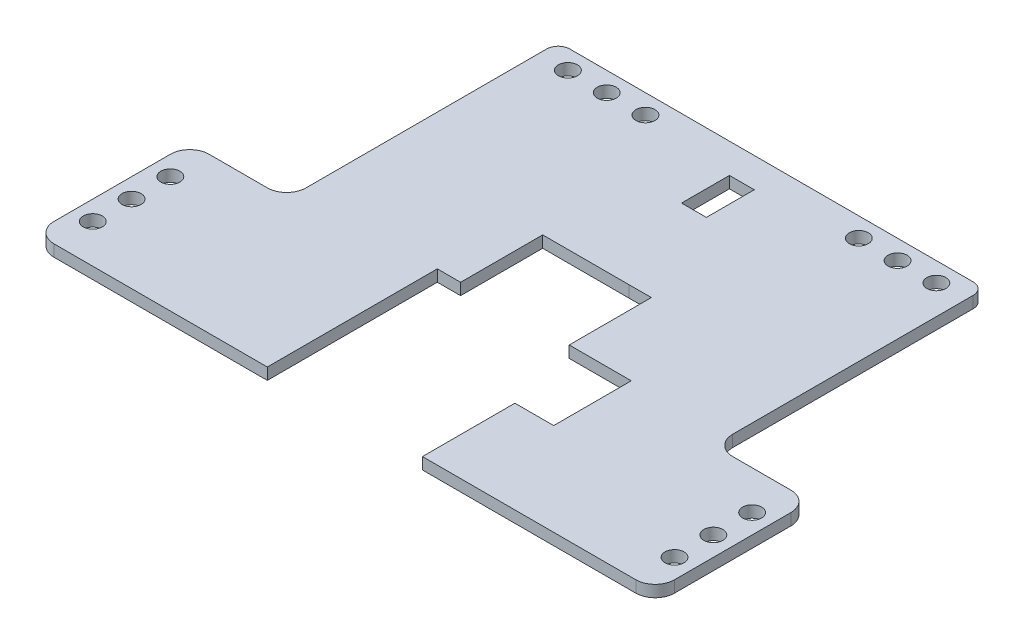
SolidWorks part; units mm, degrees
ref_plane "Front Plane" through (0, 0, 0) normal (0, 0, 1) x (1, 0, 0)
ref_plane "Top Plane" through (0, 0, 0) normal (0, 1, 0) x (1, 0, 0)
ref_plane "Right Plane" through (0, 0, 0) normal (1, 0, 0) x (0, 0, -1)
ref_plane "Plane1" through (-80, 40, 5) normal (0, -1, 0) x (-1, 0, 0)
sketch "Sketch2" plane through (0, 40, 0) normal (0, 1, 0) x (1, 0, 0)
  line L1 (20, -16.1649) -> (20, -40)
  line L4 (3.2, 50) -> (-3.2, 50)
  line L5 (-20, -40) -> (-20, 3.8351)
  line L6 (20, 3.8351) -> (30, 3.8351)
  line L8 (20, -16.1649) -> (30, -16.1649)
  line L9 (30, 3.8351) -> (30, -16.1649)
  line L10 (20, 3.8351) -> (14, 3.8351)
  line L11 (-14, 25) -> (8.2898, 25)
  line L13 (-20, 3.8351) -> (-14, 3.8351)
  line L14 (-20, 3.8351) -> (-8, 3.8351) construction
  line L15 (-14, 3.8351) -> (-14, 25)
  line L16 (14, 3.8351) -> (14, 25.023)
  line L17 (38.338, 25.023) -> (12.29, 25.023) construction
  line L18 (14, 25.023) -> (8.2898, 25)
  line L30 (45, 55) -> (45, -5)
  line L31 (50, -10) -> (65, -10)
  line L35 (20, -40) -> (75, -40)
  line L36 (80, -35) -> (80, -5)
  line L37 (75, 0) -> (60, 0)
  line L38 (55, 5) -> (55, 67)
  line L39 (52, 70) -> (10, 70)
  line L40 (10, 70) -> (-10, 70)
  line L111 (45, 55) -> (45, -5)
  line L112 (50, -10) -> (65, -10)
  line L113 (70, -15) -> (70, -25)
  line L114 (65, -30) -> (20, -30)
  line L115 (20, -30) -> (20, -40)
  line L116 (20, -40) -> (75, -40)
  line L117 (80, -35) -> (80, -5)
  line L118 (75, 0) -> (60, 0)
  line L119 (55, 5) -> (55, 67)
  line L120 (52, 70) -> (10, 70)
  line L121 (10, 70) -> (-10, 70)
  line L122 (-10, 70) -> (-52, 70)
  line L123 (-55, 67) -> (-55, 5)
  line L124 (-60, 0) -> (-75, 0)
  line L125 (-80, -5) -> (-80, -35)
  line L126 (-75, -40) -> (-20, -40)
  line L127 (-20, -40) -> (-20, -30)
  line L128 (-20, -30) -> (-65, -30)
  line L129 (-70, -25) -> (-70, -15)
  line L130 (-65, -10) -> (-50, -10)
  line L131 (-45, -5) -> (-45, 55)
  line L132 (-40, 60) -> (-15, 60)
  line L133 (-10, 55) -> (-10, 50)
  line L134 (-10, 50) -> (-3.2, 50)
  line L135 (-3.2, 50) -> (-3.2, 62.35)
  line L136 (-3.2, 62.35) -> (3.2, 62.35)
  line L137 (3.2, 62.35) -> (3.2, 50)
  line L138 (3.2, 50) -> (10, 50)
  line L139 (10, 50) -> (10, 55)
  line L140 (15, 60) -> (40, 60)
  line L146 (20, -40) -> (75, -40)
  line L147 (80, -35) -> (80, -5)
  line L148 (75, 0) -> (60, 0)
  line L149 (55, 5) -> (55, 67)
  line L150 (52, 70) -> (10, 70)
  line L151 (10, 70) -> (-10, 70)
  line L152 (-10, 70) -> (-52, 70)
  line L153 (-55, 67) -> (-55, 5)
  line L154 (-60, 0) -> (-75, 0)
  line L155 (-80, -5) -> (-80, -35)
  line L156 (-75, -40) -> (-20, -40)
  line L165 (-3.2, 50) -> (-3.2, 62.35)
  line L166 (-3.2, 62.35) -> (3.2, 62.35)
  line L167 (3.2, 62.35) -> (3.2, 50)
  line L174 (70, -15) -> (70, -25)
  line L175 (65, -30) -> (20, -30)
  line L176 (20, -30) -> (20, -40)
  line L178 (-10, 70) -> (-52, 70)
  line L180 (-55, 67) -> (-55, 5)
  line L182 (-60, 0) -> (-75, 0)
  line L184 (-80, -5) -> (-80, -35)
  line L186 (-75, -40) -> (-20, -40)
  line L188 (-20, -40) -> (-20, -30)
  line L190 (-20, -30) -> (-65, -30)
  line L191 (-70, -25) -> (-70, -15)
  line L192 (-65, -10) -> (-50, -10)
  line L193 (-45, -5) -> (-45, 55)
  line L194 (-40, 60) -> (-15, 60)
  line L195 (-10, 55) -> (-10, 50)
  line L196 (-10, 50) -> (-3.2, 50)
  line L197 (-3.2, 50) -> (-3.2, 62.35)
  line L198 (-3.2, 50) -> (-3.2, 62.35)
  line L199 (-3.2, 62.35) -> (3.2, 62.35)
  line L200 (-3.2, 62.35) -> (3.2, 62.35)
  line L201 (3.2, 62.35) -> (3.2, 50)
  line L202 (3.2, 62.35) -> (3.2, 50)
  line L203 (3.2, 50) -> (10, 50)
  line L204 (10, 50) -> (10, 55)
  line L205 (15, 60) -> (40, 60)
  circle A6 centre (47.5, 65) radius 2.45 construction
  circle A7 centre (37.5, 65) radius 2.45 construction
  circle A8 centre (27.5, 65) radius 2.45 construction
  circle A9 centre (-47.5, 65) radius 2.45 construction
  circle A10 centre (-37.5, 65) radius 2.45 construction
  circle A11 centre (-27.5, 65) radius 2.45 construction
  circle A54 centre (47.5, 65) radius 2.45
  circle A55 centre (37.5, 65) radius 2.45
  circle A56 centre (27.5, 65) radius 2.45
  circle A57 centre (-47.5, 65) radius 2.45
  circle A58 centre (-37.5, 65) radius 2.45
  circle A59 centre (-27.5, 65) radius 2.45
  circle A60 centre (-75, -30) radius 2.45 construction
  circle A61 centre (-75, -20) radius 2.45 construction
  circle A62 centre (-75, -10) radius 2.45 construction
  circle A63 centre (75, -30) radius 2.45 construction
  circle A64 centre (75, -20) radius 2.45 construction
  circle A65 centre (75, -10) radius 2.45 construction
  circle A66 centre (-75, -30) radius 2.45
  circle A67 centre (-75, -20) radius 2.45
  circle A68 centre (-75, -10) radius 2.45
  circle A69 centre (75, -30) radius 2.45
  circle A70 centre (75, -20) radius 2.45
  circle A71 centre (75, -10) radius 2.45
  arc A90 (45, -5) -> (50, -10) centre (50, -5) ccw
  arc A91 (70, -15) -> (65, -10) centre (65, -15) ccw
  arc A92 (65, -30) -> (70, -25) centre (65, -25) ccw
  arc A93 (75, -40) -> (80, -35) centre (75, -35) ccw
  arc A94 (80, -5) -> (75, 0) centre (75, -5) ccw
  arc A95 (55, 5) -> (60, 0) centre (60, 5) ccw
  arc A96 (45, -5) -> (50, -10) centre (50, -5) ccw
  arc A97 (70, -15) -> (65, -10) centre (65, -15) ccw
  arc A98 (65, -30) -> (70, -25) centre (65, -25) ccw
  arc A99 (75, -40) -> (80, -35) centre (75, -35) ccw
  arc A101 (80, -5) -> (75, 0) centre (75, -5) ccw
  arc A103 (55, 5) -> (60, 0) centre (60, 5) ccw
  arc A109 (-60, 0) -> (-55, 5) centre (-60, 5) ccw
  arc A111 (-75, 0) -> (-80, -5) centre (-75, -5) ccw
  arc A113 (-80, -35) -> (-75, -40) centre (-75, -35) ccw
  arc A115 (-70, -25) -> (-65, -30) centre (-65, -25) ccw
  arc A116 (-65, -10) -> (-70, -15) centre (-65, -15) ccw
  arc A117 (-50, -10) -> (-45, -5) centre (-50, -5) ccw
  arc A118 (-40, 60) -> (-45, 55) centre (-40, 55) ccw
  arc A119 (-10, 55) -> (-15, 60) centre (-15, 55) ccw
  arc A120 (15, 60) -> (10, 55) centre (15, 55) ccw
  arc A121 (45, 55) -> (40, 60) centre (40, 55) ccw
  arc A122 (-52, 70) -> (-55, 67) centre (-52, 67) ccw
  arc A123 (-52, 70) -> (-55, 67) centre (-52, 67) ccw
  arc A124 (-60, 0) -> (-55, 5) centre (-60, 5) ccw
  arc A125 (-75, 0) -> (-80, -5) centre (-75, -5) ccw
  arc A126 (-80, -35) -> (-75, -40) centre (-75, -35) ccw
  arc A127 (-70, -25) -> (-65, -30) centre (-65, -25) ccw
  arc A128 (-65, -10) -> (-70, -15) centre (-65, -15) ccw
  arc A129 (-50, -10) -> (-45, -5) centre (-50, -5) ccw
  arc A130 (-40, 60) -> (-45, 55) centre (-40, 55) ccw
  arc A131 (-10, 55) -> (-15, 60) centre (-15, 55) ccw
  arc A132 (15, 60) -> (10, 55) centre (15, 55) ccw
  arc A133 (45, 55) -> (40, 60) centre (40, 55) ccw
  arc A137 (75, -40) -> (80, -35) centre (75, -35) ccw
  arc A138 (80, -5) -> (75, 0) centre (75, -5) ccw
  arc A139 (55, 5) -> (60, 0) centre (60, 5) ccw
  arc A142 (-60, 0) -> (-55, 5) centre (-60, 5) ccw
  arc A143 (-75, 0) -> (-80, -5) centre (-75, -5) ccw
  arc A144 (-80, -35) -> (-75, -40) centre (-75, -35) ccw
  arc A167 (-52, 70) -> (-55, 67) centre (-52, 67) ccw
  arc A168 (-52, 70) -> (-55, 67) centre (-52, 67) ccw
  arc A169 (55, 67) -> (52, 70) centre (52, 67) ccw
  arc A170 (55, 67) -> (52, 70) centre (52, 67) ccw
  arc A174 (55, 67) -> (52, 70) centre (52, 67) ccw
  arc A175 (55, 67) -> (52, 70) centre (52, 67) ccw
  point P31 (0, 25)
  dimension "D2" = 21.1649
  dimension "D3" = 10
  dimension "D4" = 20
  dimension "D1" = 0
  dimension "D5" = 0
extrude "Boss-Extrude1" add sketch "Sketch2" along normal blind 3
